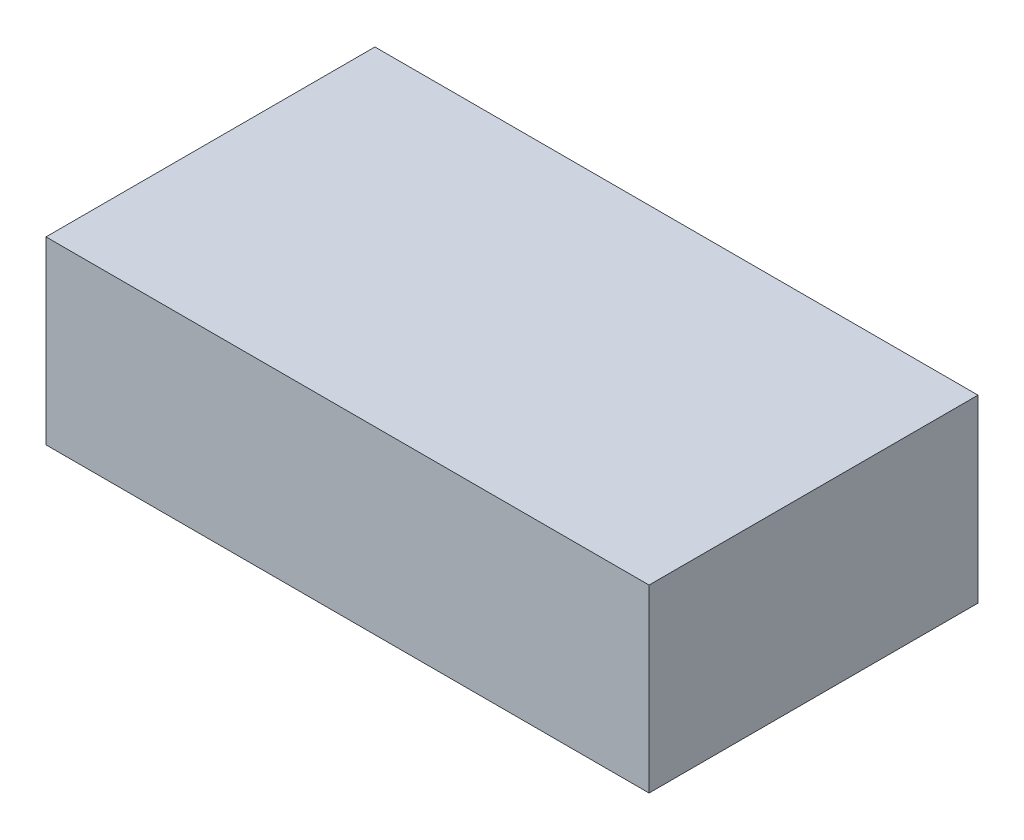
SolidWorks part; units mm, degrees
ref_plane "Front" through (0, 0, 0) normal (0, 0, 1) x (1, 0, 0)
ref_plane "Top" through (0, 0, 0) normal (0, 1, 0) x (1, 0, 0)
ref_plane "Right" through (0, 0, 0) normal (1, 0, 0) x (0, 0, -1)
sketch "草图1" plane through (0, 0, 0) normal (0, 1, 0) x (1, 0, 0)
  line L1 (-38.5, 21) -> (38.5, 21)
  line L2 (-38.5, 21) -> (-38.5, -21)
  line L3 (-38.5, -21) -> (38.5, -21)
  line L4 (38.5, 21) -> (38.5, -21)
  line L5 (-38.5, 21) -> (38.5, -21) construction
  line L6 (-38.5, -21) -> (38.5, 21) construction
  point P0 (0, 0)
  dimension "D1" = 42
  dimension "D2" = 77
extrude "凸台-拉伸1" add sketch "草图1" along normal blind 23
